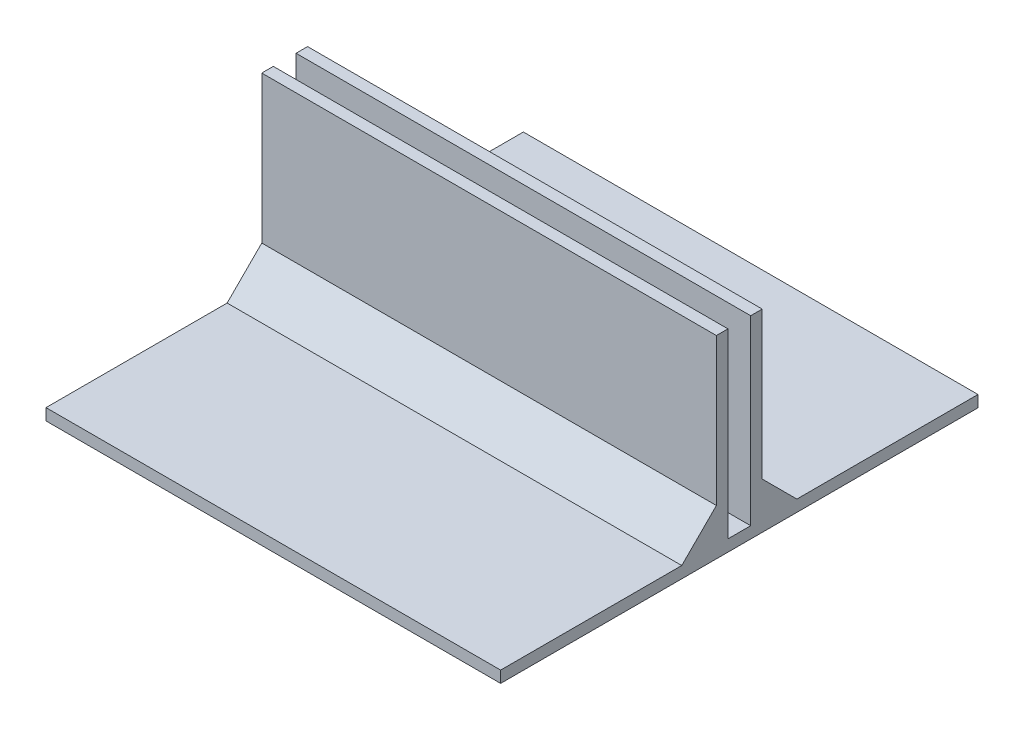
SolidWorks part; units mm, degrees
ref_plane "Front Plane" through (0, 0, 0) normal (0, 0, 1) x (1, 0, 0)
ref_plane "Top Plane" through (0, 0, 0) normal (0, 1, 0) x (1, 0, 0)
ref_plane "Right Plane" through (0, 0, 0) normal (1, 0, 0) x (0, 0, -1)
sketch "Sketch1" plane through (0, 0, 0) normal (0, 1, 0) x (1, 0, 0)
  line L1 (-50, -52.5) -> (50, -52.5)
  line L2 (-50, -52.5) -> (-50, 52.5)
  line L3 (-50, 52.5) -> (50, 52.5)
  line L4 (50, -52.5) -> (50, 52.5)
  line L5 (-50, -52.5) -> (50, 52.5) construction
  line L6 (-50, 52.5) -> (50, -52.5) construction
  point P0 (0, 0)
  dimension "D1" = 105
  dimension "D2" = 100
extrude "Boss-Extrude1" add sketch "Sketch1" along normal blind 2.54
sketch "Sketch2" plane through (0, 2.54, 0) normal (0, 1, 0) x (1, 0, 0)
  line L0 (50, -52.5) -> (50, 52.5) construction
  line L1 (-50, -2.5) -> (50, -2.5)
  line L2 (-50, -2.5) -> (-50, 2.5)
  line L3 (-50, 2.5) -> (50, 2.5)
  line L4 (50, -2.5) -> (50, 2.5)
  line L5 (-50, -2.5) -> (50, 2.5) construction
  line L6 (-50, 2.5) -> (50, -2.5) construction
  line L8 (-50, -5.04) -> (50, -5.04)
  line L9 (-50, -5.04) -> (-50, 5.04)
  line L10 (-50, 5.04) -> (50, 5.04)
  line L11 (50, -5.04) -> (50, 5.04)
  line L12 (-50, -5.04) -> (50, 5.04) construction
  line L13 (-50, 5.04) -> (50, -5.04) construction
  point P0 (0, 0)
  point P8 (0, 0)
  line M4 (50, -52.5) -> (50, 52.5)
  line M6 (-50, 52.5) -> (-50, -52.5)
  dimension "D1" = 5
  dimension "D2" = 2.54
extrude "Boss-Extrude2" add sketch "Sketch2" along normal blind 40 contours L10 L3 M6 M4 | L8 L1 M6 M4
chamfer "Chamfer1" distance 7.62 angle 45 2 edges at (0, 2.54, -5.04) (0, 2.54, 5.04)
